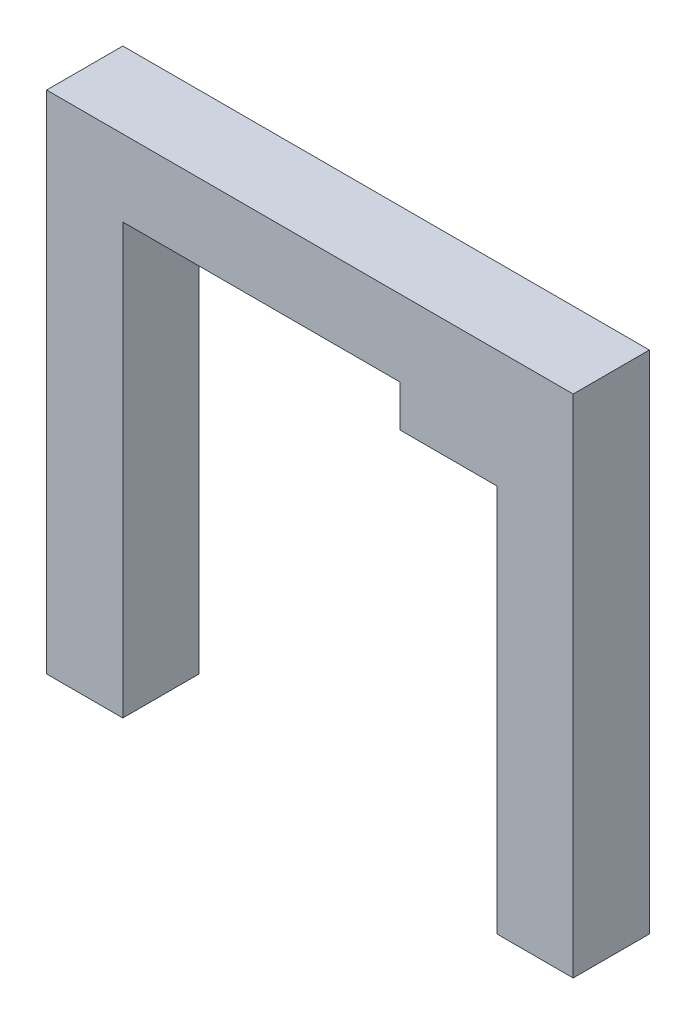
SolidWorks part; units mm, degrees
material "ﾁｰｸ材"
ref_plane "正面" through (0, 0, 0) normal (0, 0, 1) x (1, 0, 0)
ref_plane "平面" through (0, 0, 0) normal (0, 1, 0) x (1, 0, 0)
ref_plane "右側面" through (0, 0, 0) normal (1, 0, 0) x (0, 0, -1)
sketch "ｽｹｯﾁ1" plane through (0, 0, 0) normal (0, 0, 1) x (1, 0, 0)
  line L0 (0, 0) -> (0, 31)
  line L1 (0, 0) -> (-5.5, 0)
  line L2 (-5.5, 0) -> (-5.5, 36.5)
  line L3 (-5.5, 36.5) -> (32.5, 36.5)
  line L4 (32.5, 36.5) -> (32.5, 0)
  line L5 (32.5, 0) -> (27, 0)
  line L9 (27, 28) -> (20, 28)
  line L10 (20, 28) -> (20, 31)
  line L11 (20, 31) -> (0, 31)
  line L12 (27, 28) -> (27, 0)
  dimension "D1" = 20
  dimension "D2" = 31
  dimension "D3" = 5.5
  dimension "D4" = 5.5
  dimension "D5" = 5.5
  dimension "D6" = 3
  dimension "D7" = 7
extrude "ﾎﾞｽ - 押し出し1" add sketch "ｽｹｯﾁ1" along normal blind 5.5
